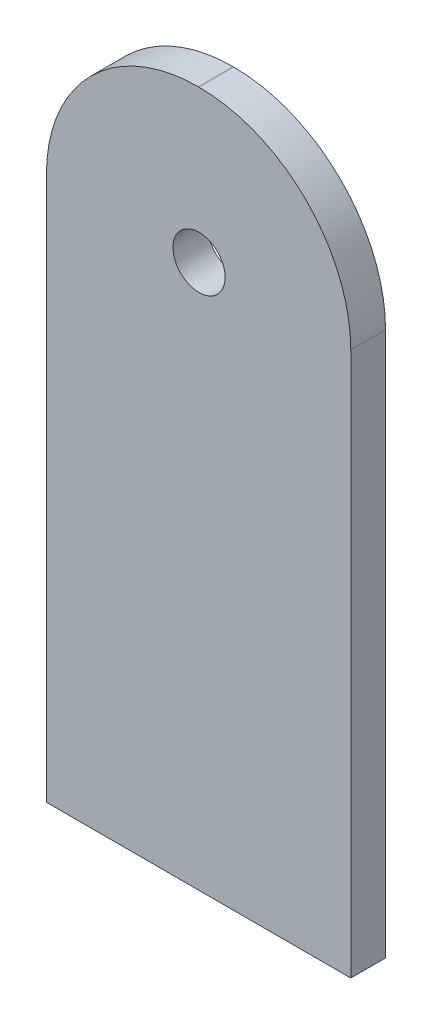
SolidWorks part; units mm, degrees
ref_plane "Спереди" through (0, 0, 0) normal (0, 0, 1) x (1, 0, 0)
ref_plane "Сверху" through (0, 0, 0) normal (0, 1, 0) x (1, 0, 0)
ref_plane "Справа" through (0, 0, 0) normal (1, 0, 0) x (0, 0, -1)
sketch "Эскиз1" plane through (0, 0, 0) normal (0, 0, 1) x (1, 0, 0)
  line L1 (-17.5, 0) -> (17.5, 0)
  line L2 (-17.5, 0) -> (-17.5, 62.55)
  line L3 (-0.05, 80) -> (0.05, 80)
  line L4 (17.5, 0) -> (17.5, 62.55)
  line L5 (-17.5, 0) -> (17.5, 80) construction
  line L6 (-17.5, 80) -> (17.5, 0) construction
  arc A0 (0.05, 80) -> (17.5, 62.55) centre (0.05, 62.55) cw
  arc A1 (-17.5, 62.55) -> (-0.05, 80) centre (-0.05, 62.55) cw
  circle A2 centre (0.05, 62.55) radius 3
  point P0 (0, 40)
  point P5 (0, 0)
  dimension "D3" = 17.45
  dimension "D4" = 6
  dimension "D1" = 35
  dimension "D2" = 80
extrude "Бобышка-Вытянуть1" add sketch "Эскиз1" along normal blind 4 contours L4 A0 L3 A1 L2 L1
